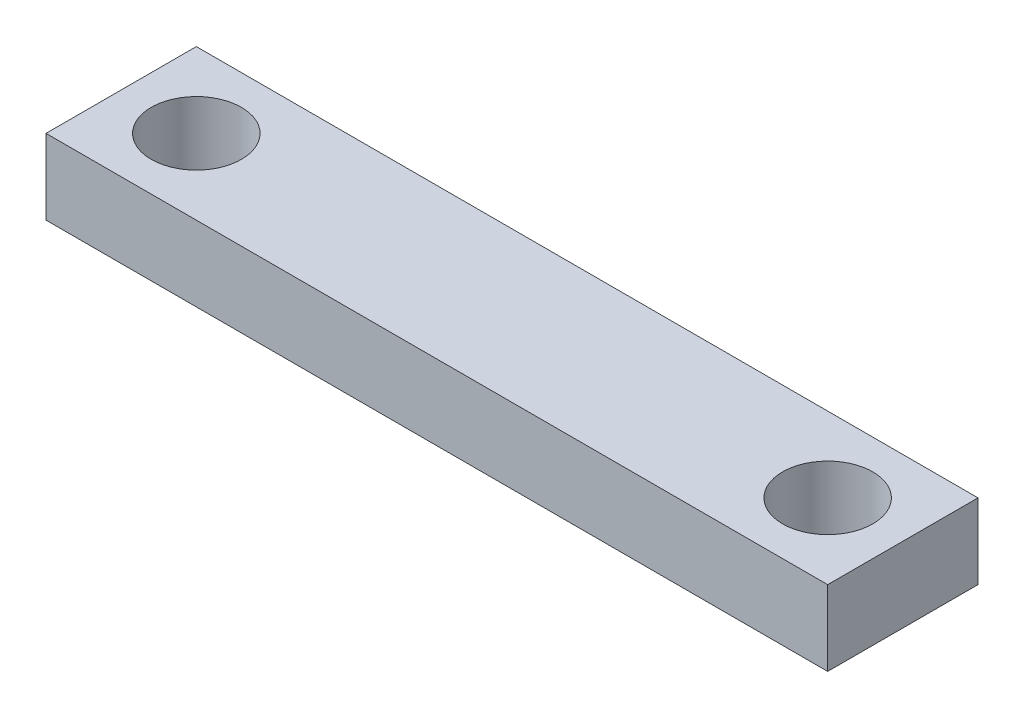
SolidWorks part; units mm, degrees
ref_plane "Front Plane" through (0, 0, 0) normal (0, 0, 1) x (1, 0, 0)
ref_plane "Top Plane" through (0, 0, 0) normal (0, 1, 0) x (1, 0, 0)
ref_plane "Right Plane" through (0, 0, 0) normal (1, 0, 0) x (0, 0, -1)
sketch "Sketch1" plane through (0, 0, 0) normal (0, 1, 0) x (1, 0, 0)
  line L1 (26, 5) -> (-26, 5)
  line L2 (26, 5) -> (26, -5)
  line L3 (26, -5) -> (-26, -5)
  line L4 (-26, 5) -> (-26, -5)
  line L5 (26, 5) -> (-26, -5) construction
  line L6 (26, -5) -> (-26, 5) construction
  circle A0 centre (-21, 0) radius 3
  circle A1 centre (21, 0) radius 3
  point P0 (0, 0)
  dimension "D3" = 6
  dimension "D1" = 10
  dimension "D2" = 52
  dimension "D4" = 5
  dimension "D5" = 5
  dimension "D6" = 42
extrude "Boss-Extrude1" add sketch "Sketch1" along normal mid plane 5
equation "\"D2@Sketch1\"= \"D6@Sketch1\" + 10mm"
